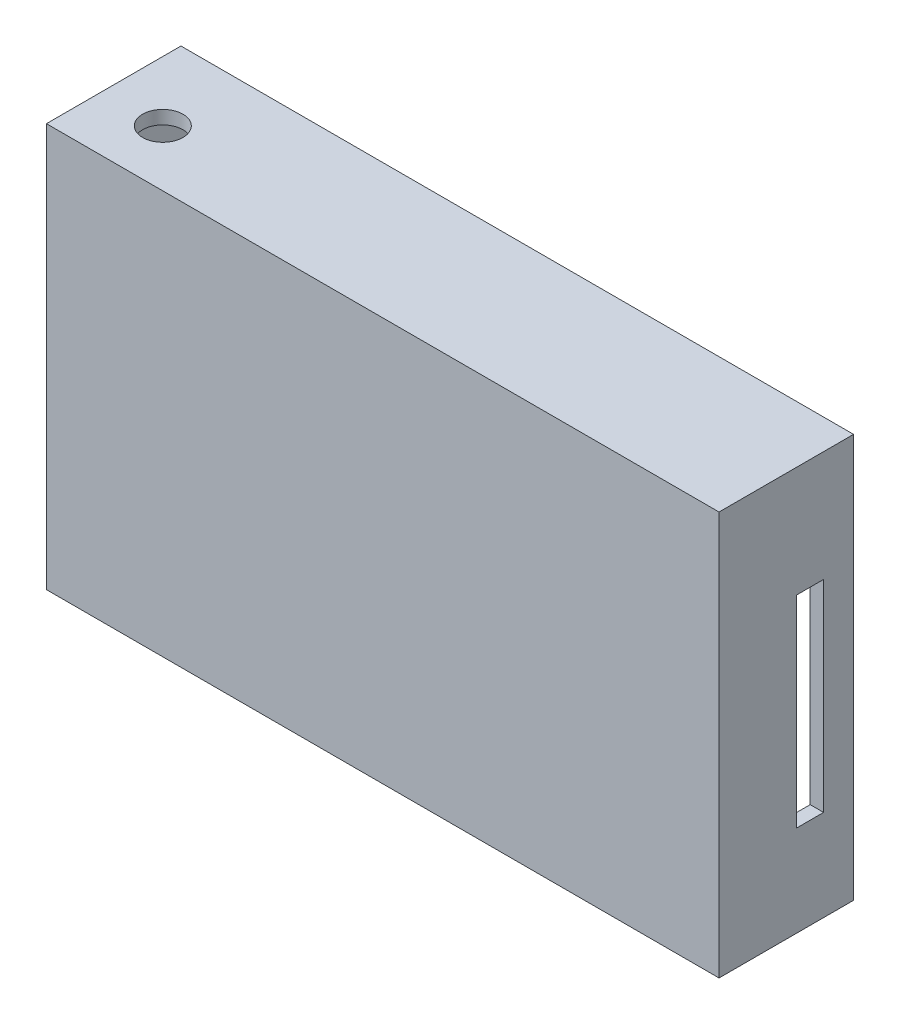
SolidWorks part; units mm, degrees
ref_plane "Front Plane" through (0, 0, 0) normal (0, 0, 1) x (1, 0, 0)
ref_plane "Top Plane" through (0, 0, 0) normal (0, 1, 0) x (1, 0, 0)
ref_plane "Right Plane" through (0, 0, 0) normal (1, 0, 0) x (0, 0, -1)
sketch "Sketch1" plane through (0, 0, 0) normal (0, 0, 1) x (1, 0, 0)
  line L1 (-25, 15) -> (25, 15)
  line L2 (-25, 15) -> (-25, -15)
  line L3 (-25, -15) -> (25, -15)
  line L4 (25, 15) -> (25, -15)
  line L5 (-25, 15) -> (25, -15) construction
  line L6 (-25, -15) -> (25, 15) construction
  point P0 (0, 0)
  dimension "D1" = 50
  dimension "D2" = 30
extrude "Boss-Extrude1" add sketch "Sketch1" along normal blind 10
shell "Shell4" thickness 1
ref_plane "Plane1" through (35, 0, 0) normal (1, 0, 0) x (0, 0, -1)
sketch "Sketch9" plane through (35, 0, 0) normal (1, 0, 0) x (0, 0, -1)
  line L1 (-4.226, 6.773) -> (-2.226, 6.773)
  line L2 (-4.226, 6.773) -> (-4.226, -8.227)
  line L3 (-4.226, -8.227) -> (-2.226, -8.227)
  line L4 (-2.226, 6.773) -> (-2.226, -8.227)
  line L5 (-4.226, 6.773) -> (-2.226, -8.227) construction
  line L6 (-4.226, -8.227) -> (-2.226, 6.773) construction
  point P0 (-3.226, -0.727)
extrude "Cut-Extrude5" cut sketch "Sketch9" against normal through all
ref_plane "Plane2" through (0, 25, 0) normal (0, 1, 0) x (1, 0, 0)
sketch "Sketch10" plane through (0, 25, 0) normal (0, 1, 0) x (1, 0, 0)
  circle A0 centre (-20.5349, -5.8154) radius 1.5
  point P2 (-20.5349, -5.8154)
  dimension "D1" = 3
extrude "Cut-Extrude6" cut sketch "Sketch10" against normal blind 21
